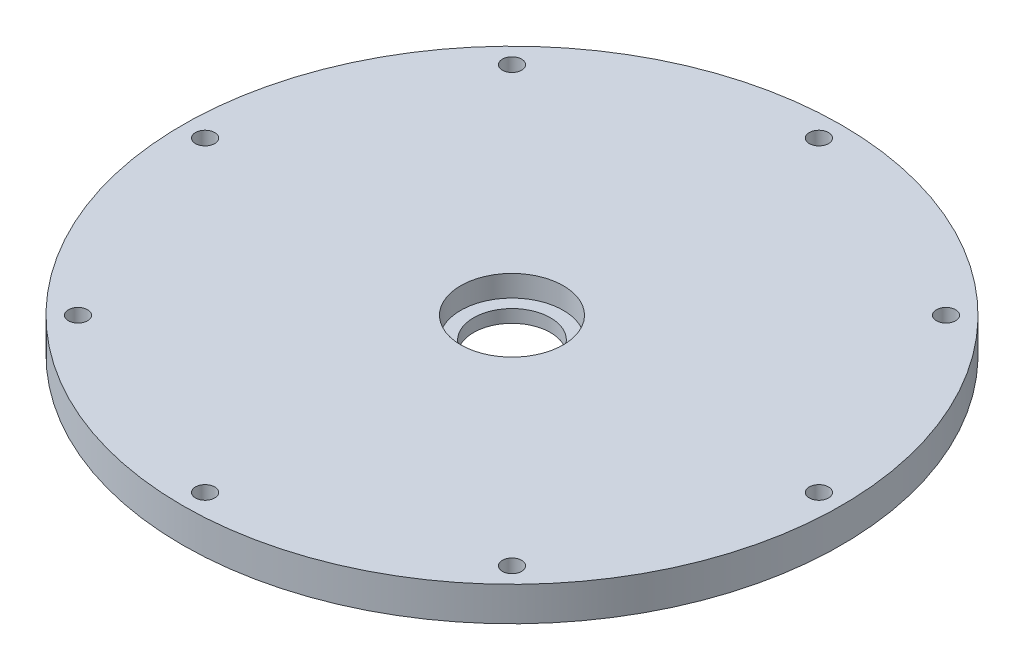
SolidWorks part; units mm, degrees
ref_plane "Front Plane" through (0, 0, 0) normal (0, 0, 1) x (1, 0, 0)
ref_plane "Top Plane" through (0, 0, 0) normal (0, 1, 0) x (1, 0, 0)
ref_plane "Right Plane" through (0, 0, 0) normal (1, 0, 0) x (0, 0, -1)
sketch "Sketch1" plane through (0, 0, 0) normal (0, 1, 0) x (1, 0, 0)
  circle A0 centre (0, 0) radius 77.1
extrude "Boss-Extrude1" add sketch "Sketch1" along normal blind 8
sketch "Sketch2" plane through (0, 8, 0) normal (0, 1, 0) x (1, 0, 0)
  circle A0 centre (0, 0) radius 71.8 construction
  circle A1 centre (0, 71.8) radius 2.25
  circle A2 centre (50.7703, 50.7703) radius 2.25
  circle A3 centre (71.8, 0) radius 2.25
  circle A4 centre (50.7703, -50.7703) radius 2.25
  circle A5 centre (0, -71.8) radius 2.25
  circle A6 centre (-50.7703, -50.7703) radius 2.25
  circle A7 centre (-71.8, 0) radius 2.25
  circle A8 centre (-50.7703, 50.7703) radius 2.25
  point P14 (0, 0)
  dimension "D3" = 8
extrude "Cut-Extrude1" cut sketch "Sketch2" against normal through all
sketch "Sketch3" plane through (0, 0, 0) normal (0, -1, 0) x (1, 0, 0)
  circle A0 centre (0, 0) radius 60 construction
  circle A1 centre (60, 0) radius 3
  circle A2 centre (57.9555, -15.5291) radius 3
  circle A3 centre (51.9615, -30) radius 3
  circle A4 centre (42.4264, -42.4264) radius 3
  circle A5 centre (30, -51.9615) radius 3
  circle A6 centre (15.5291, -57.9555) radius 3
  circle A7 centre (0, -60) radius 3
  circle A8 centre (-15.5291, -57.9555) radius 3
  circle A9 centre (-30, -51.9615) radius 3
  circle A10 centre (-42.4264, -42.4264) radius 3
  circle A11 centre (-51.9615, -30) radius 3
  circle A12 centre (-57.9555, -15.5291) radius 3
  circle A13 centre (-60, 0) radius 3
  circle A14 centre (-57.9555, 15.5291) radius 3
  circle A15 centre (-51.9615, 30) radius 3
  circle A16 centre (-42.4264, 42.4264) radius 3
  circle A17 centre (-30, 51.9615) radius 3
  circle A18 centre (-15.5291, 57.9555) radius 3
  circle A19 centre (0, 60) radius 3
  circle A20 centre (15.5291, 57.9555) radius 3
  circle A21 centre (30, 51.9615) radius 3
  circle A22 centre (42.4264, 42.4264) radius 3
  circle A23 centre (51.9615, 30) radius 3
  circle A24 centre (57.9555, 15.5291) radius 3
  point P14 (0, 0)
  dimension "D1" = 120
  dimension "D2" = 6
  dimension "D3" = 24
extrude "Cut-Extrude2" cut sketch "Sketch3" against normal blind 5
sketch "Sketch4" plane through (0, 8, 0) normal (0, 1, 0) x (1, 0, 0)
  circle A0 centre (0, 0) radius 12
  dimension "D1" = 24
extrude "Cut-Extrude3" cut sketch "Sketch4" against normal blind 5
sketch "Sketch5" plane through (0, 3, 0) normal (0, 1, 0) x (1, 0, 0)
  circle A0 centre (0, 0) radius 9
  dimension "D1" = 18
extrude "Cut-Extrude4" cut sketch "Sketch5" against normal blind 5
equation "\"N_pin\"= 24"
equation "\"R_pin\"= 60"
equation "\"d_pin\"= 13"
equation "\"e\"= 1.5"
equation "\"t_disk\"= 5"
equation "\"N_outpin\"= 8"
equation "\"R_outpin\"= 34"
equation "\"d_outpin\"= 13"
equation "\"N_lobes\"= \"N_pin\" - 1"
equation "\"d_outhole\"= \"d_outpin\" + 2 * \"e\""
equation "\"ratio\"= \"N_lobes\""
equation "\"d_center\"= 24"
equation "\"a_hole1\"= 0 / \"N_lobes\""
equation "\"a_hole2\"= 360 / \"N_disk\" / \"N_lobes\""
equation "\"a_hole3\"= 720 / \"N_disk\" / \"N_lobes\""
equation "\"N_disk\"= 3"
equation "\"t_gap\"= 1"
equation "\"L_stack\"= \"N_disk\" * \"t_disk\" + (\"N_disk\" - 1) * \"t_gap\""
equation "\"d_pinshaft\"= 6"
equation "\"d_ecc\"= 15"
equation "\"d_outbrg\"= 47"
equation "\"w_outbrg\"= 7"
equation "\"d_outshaft\"= 35"
equation "\"w_brg\"= 5"
equation "\"c_run\"= 0.5"
equation "\"c_ax\"= \"t_gap\""
equation "\"D_pocket\"= 2 * \"R_pin\" + \"d_pin\" + 2 * \"c_run\""
equation "\"h_pocket\"= \"L_stack\" + 2 * \"c_ax\""
equation "\"t_floor\"= 8"
equation "\"d_insert\"= 5.6"
equation "\"N_bolt\"= 8"
equation "\"R_bolt\"= \"D_pocket\" / 2 + 2 + \"d_insert\" / 2"
equation "\"D_housing\"= 2 * (\"R_bolt\" + \"d_insert\" / 2 + 2.5)"
equation "\"D1@Sketch1\"=\"D_housing\""
equation "\"D1@Boss-Extrude1\"=\"t_floor\""
equation "\"D1@Sketch2\"=\"R_bolt\"*2"
equation "\"D3@Sketch2\"=\"N_bolt\""
equation "\"D1@Sketch3\"=\"R_pin\"*2"
equation "\"D2@Sketch3\"=\"d_pinshaft\""
equation "\"D3@Sketch3\"=\"N_pin\""
equation "\"D1@Cut-Extrude2\"=\"t_floor\"-3"
equation "\"D1@Sketch4\"=\"d_center\""
equation "\"D1@Cut-Extrude3\"=\"w_brg\""
equation "\"D1@Sketch5\"=\"d_ecc\"+3"
